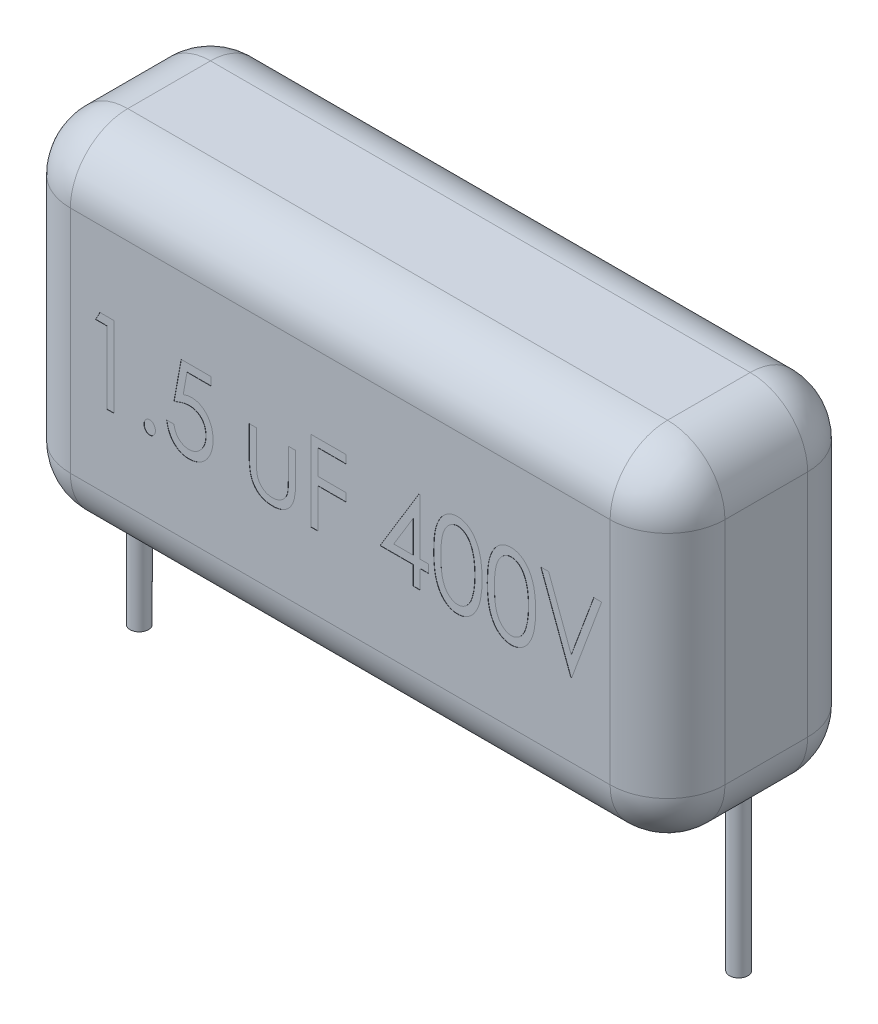
SolidWorks part; units mm, degrees
ref_plane "Front Plane" through (0, 0, 0) normal (0, 0, 1) x (1, 0, 0)
ref_plane "Top Plane" through (0, 0, 0) normal (0, 1, 0) x (1, 0, 0)
ref_plane "Right Plane" through (0, 0, 0) normal (1, 0, 0) x (0, 0, -1)
sketch "Sketch1" plane through (0, 0, 0) normal (1, 0, 0) x (0, 0, -1)
  line L1 (-1.8, 7.5) -> (1.8, 7.5)
  line L2 (-4.3, 5) -> (-4.3, -5)
  line L3 (-1.8, -7.5) -> (1.8, -7.5)
  line L4 (4.3, 5) -> (4.3, -5)
  line L5 (-4.3, 7.5) -> (4.3, -7.5) construction
  line L6 (-4.3, -7.5) -> (4.3, 7.5) construction
  arc A0 (4.3, -5) -> (1.8, -7.5) centre (1.8, -5) cw
  arc A1 (-1.8, -7.5) -> (-4.3, -5) centre (-1.8, -5) cw
  arc A2 (4.3, 5) -> (1.8, 7.5) centre (1.8, 5) ccw
  arc A3 (-4.3, 5) -> (-1.8, 7.5) centre (-1.8, 5) cw
  point P0 (0, 0)
  dimension "D3" = 2.5
  dimension "D1" = 15
  dimension "D2" = 8.6
extrude "Boss-Extrude1" add sketch "Sketch1" along normal mid plane 28.5
fillet "Fillet1" radius 2.5 16 edges at (-14.25, 0, -4.3) (-14.25, 6.7678, -3.5678) (-14.25, 7.5, 0) (-14.25, 6.7678, 3.5678) (-14.25, 0, 4.3) (-14.25, -6.7678, 3.5678) (-14.25, -7.5, 0) (-14.25, -6.7678, -3.5678) (14.25, -7.5, 0) (14.25, -6.7678, 3.5678) (14.25, 0, 4.3) (14.25, 6.7678, 3.5678) (14.25, 7.5, 0) (14.25, 6.7678, -3.5678) (14.25, 0, -4.3) (14.25, -6.7678, -3.5678)
sketch "Sketch2" plane through (0, 0, 0) normal (0, 1, 0) x (1, 0, 0)
  line L0 (0, 7.3846) -> (0, -6.8387) construction
  circle A0 centre (13.05, 0) radius 0.4
  circle A1 centre (-13.05, 0) radius 0.4
  dimension "D1" = 0.8
  dimension "D2" = 26.1
extrude "Boss-Extrude2" add sketch "Sketch2" against normal blind 13.5
sketch "Sketch4" plane through (0, 0, 4.3) normal (0, 0, 1) x (1, 0, 0)
  line L0 (-11.235, -1.7932) -> (11.4074, -1.7932) construction
  text T0 "1.5 uF 400V" font "Century Gothic" height 3.5
extrude "Cut-Extrude1" cut sketch "Sketch4" against normal blind 0.01
